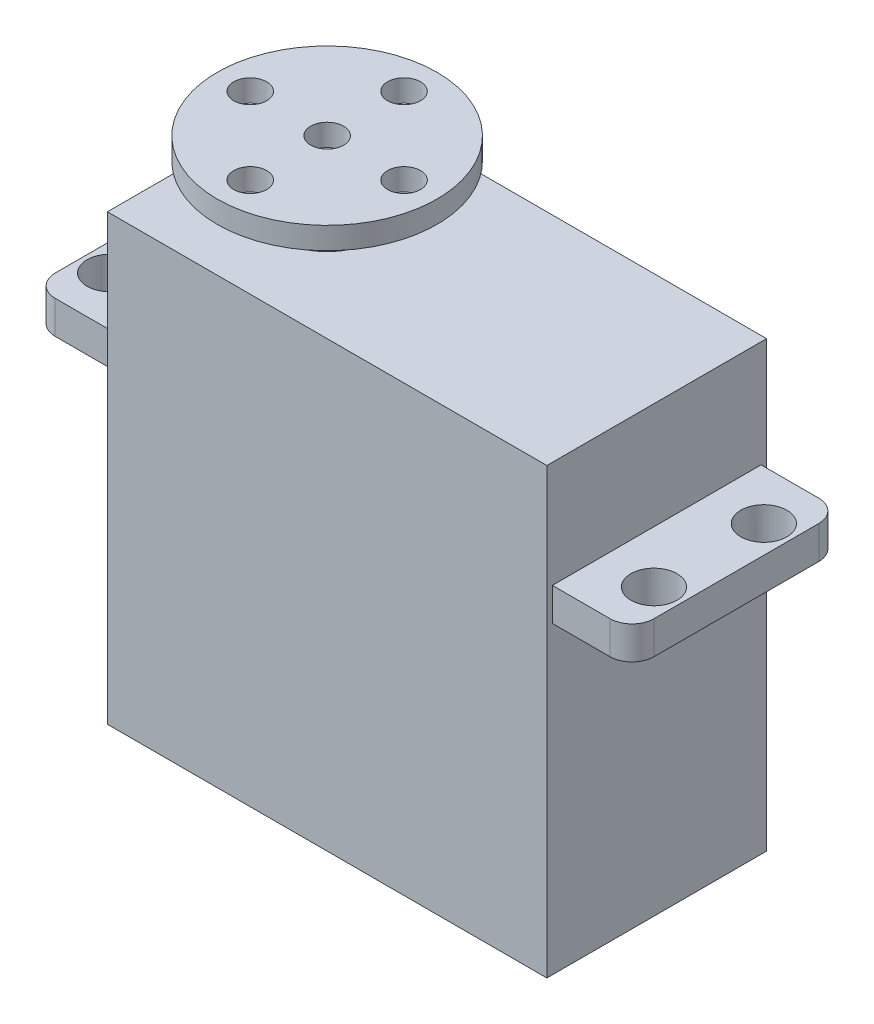
SolidWorks part; units mm, degrees
ref_plane "前视基准面" through (0, 0, 0) normal (0, 0, 1) x (1, 0, 0)
ref_plane "上视基准面" through (0, 0, 0) normal (0, 1, 0) x (1, 0, 0)
ref_plane "右视基准面" through (0, 0, 0) normal (1, 0, 0) x (0, 0, -1)
other "Configuration Table"
sketch "草图1" plane through (0, 0, 0) normal (0, 0, 1) x (1, 0, 0)
  line L5 (-20, 13.85) -> (20, 13.85)
  line L6 (-20, 13.85) -> (-20, -13.85)
  line L7 (-20, -13.85) -> (20, -13.85)
  line L8 (20, 13.85) -> (20, -13.85)
  line L9 (-20, 13.85) -> (20, -13.85) construction
  line L10 (-20, -13.85) -> (20, 13.85) construction
  point P0 (0, 0)
  dimension "D1" = 40
  dimension "D2" = 27.7
extrude "凸台-拉伸1" add sketch "草图1" along normal mid plane 20
sketch "草图3" plane through (0, 13.85, 0) normal (0, 1, 0) x (1, 0, 0)
  line L1 (-27.25, 9.5) -> (27.25, 9.5)
  line L2 (-27.25, 9.5) -> (-27.25, -9.5)
  line L3 (-27.25, -9.5) -> (27.25, -9.5)
  line L4 (27.25, 9.5) -> (27.25, -9.5)
  line L5 (-27.25, 9.5) -> (27.25, -9.5) construction
  line L6 (-27.25, -9.5) -> (27.25, 9.5) construction
  line L7 (-20, 10) -> (20, 10)
  line L8 (-20, 10) -> (-20, -10)
  line L9 (-20, -10) -> (20, -10)
  line L10 (20, 10) -> (20, -10)
  line L11 (-20, 10) -> (20, -10) construction
  line L12 (-20, -10) -> (20, 10) construction
  point P0 (0, 0)
  point P5 (0, 0)
  dimension "D1" = 54.5
  dimension "D2" = 19
extrude "凸台-拉伸2" add sketch "草图3" along normal blind 3 contours L7 L10 L9 L8 | L1 L4 L3 L2
fillet "圆角1" radius 2 4 edges at (-27.25, 15.35, -9.5) (27.25, 15.35, -9.5) (27.25, 15.35, 9.5) (-27.25, 15.35, 9.5)
sketch "草图4" plane through (0, 16.85, 0) normal (0, 1, 0) x (1, 0, 0)
  line L4 (20, 10) -> (-20, 10)
  line L5 (20, -10) -> (20, 10)
  line L6 (-20, -10) -> (20, -10)
  line L7 (-20, 10) -> (-20, -10)
  line L8 (20, 10) -> (-20, 10)
  line L9 (20, -10) -> (20, 10)
  line L10 (-20, -10) -> (20, -10)
  line L11 (-20, 10) -> (-20, -10)
  dimension "D1" = 0
extrude "凸台-拉伸3" add sketch "草图4" along normal blind 9.7
sketch "草图5" plane through (0, 16.85, 0) normal (0, 1, 0) x (1, 0, 0)
  line L0 (-27.25, 0) -> (27.25, 0) construction
  line L1 (-27.25, 7.5) -> (-27.25, -7.5) construction
  line L2 (27.25, 7.5) -> (27.25, -7.5) construction
  line L3 (0, 10) -> (0, -10) construction
  line L4 (20, 10) -> (-20, 10) construction
  line L5 (-20, -10) -> (20, -10) construction
  circle A0 centre (-24.75, 5) radius 2.1
  circle A1 centre (-24.75, -5) radius 2.1
  circle A2 centre (24.75, -5) radius 2.1
  circle A3 centre (24.75, 5) radius 2.1
  dimension "D1" = 4.2
  dimension "D3" = 10
  dimension "D2" = 49.5
extrude "切除-拉伸1" cut sketch "草图5" against normal through all
sketch "草图6" plane through (0, 26.55, 0) normal (0, 1, 0) x (1, 0, 0)
  line L0 (-20, 0) -> (20, 0) construction
  line L1 (-20, 9.5) -> (-20, -9.5) construction
  line L2 (20, -9.5) -> (20, 9.5) construction
  line L3 (-20, 10) -> (-20, -10) construction
  circle A0 centre (-10, 0) radius 4.45
  dimension "D1" = 10
  dimension "D2" = 8.9
extrude "凸台-拉伸4" add sketch "草图6" along normal blind 4
sketch "草图8" plane through (0, 30.55, 0) normal (0, 1, 0) x (1, 0, 0)
  circle A0 centre (-10, 0) radius 10
  circle A1 centre (-10, 0) radius 7 construction
  circle A2 centre (-10, 7) radius 1.5
  circle A3 centre (-3, 0) radius 1.5
  circle A4 centre (-10, -7) radius 1.5
  circle A5 centre (-17, 0) radius 1.5
  circle A6 centre (-10, 0) radius 1.5
  dimension "D1" = 20
  dimension "D2" = 14
  dimension "D3" = 3
extrude "凸台-拉伸5" add sketch "草图8" along normal blind 2 separate body
